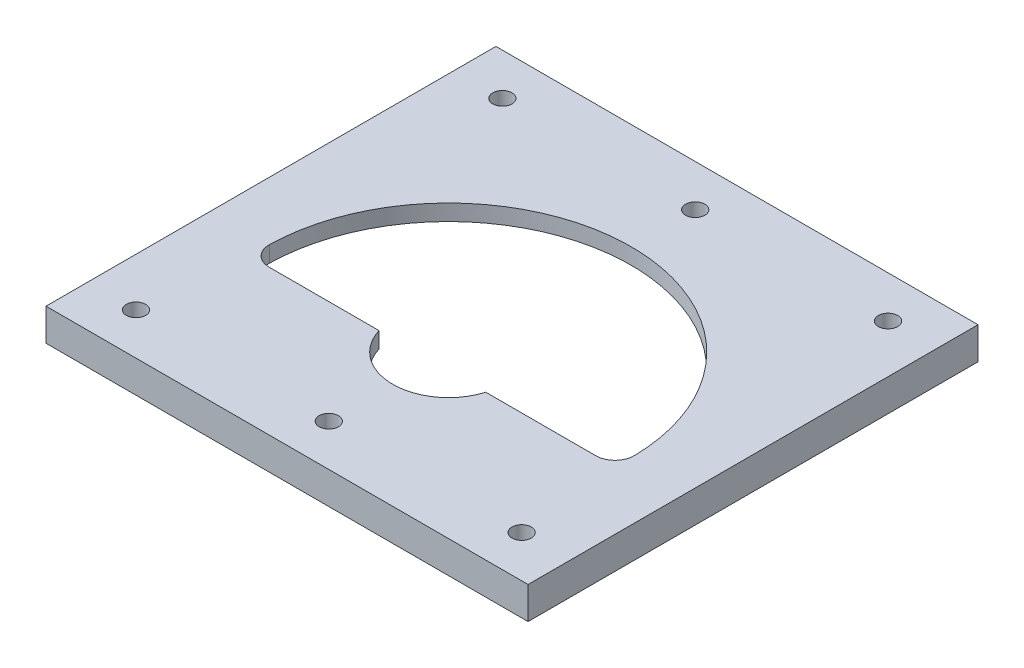
SolidWorks part; units mm, degrees
ref_plane "Front" through (0, 0, 0) normal (0, 0, 1) x (1, 0, 0)
ref_plane "Top" through (0, 0, 0) normal (0, 1, 0) x (1, 0, 0)
ref_plane "Right" through (0, 0, 0) normal (1, 0, 0) x (0, 0, -1)
sketch "Sketch1" plane through (0, 0, 0) normal (0, 1, 0) x (1, 0, 0)
  line L6 (-37.5, -25.1175) -> (37.5, -25.1175)
  line L8 (-37.5, -25.1175) -> (-37.5, 44.8825)
  line L9 (-37.5, 44.8825) -> (37.5, 44.8825)
  line L10 (37.5, -25.1175) -> (37.5, 44.8825)
  line L12 (0, 0) -> (0, 12.0208) construction
  line L13 (-25.41, -7) -> (-11.1616, -7) construction
  line L14 (11.1616, -7) -> (25.41, -7) construction
  line L15 (-12.0208, 12.0208) -> (12.0208, 12.0208) construction
  line L16 (-25.41, -7.5) -> (-11.4348, -7.5) construction
  line L17 (11.4348, -7.5) -> (25.41, -7.5) construction
  line L18 (-25.41, -2.5) -> (-8.307, -2.5)
  line L19 (8.307, -2.5) -> (25.41, -2.5)
  circle A4 centre (0, 0) radius 3.175 construction
  circle A5 centre (12.0208, 12.0208) radius 4.7625 construction
  circle A6 centre (-12.0208, 12.0208) radius 4.7625 construction
  arc A7 (32.9086, 0.6476) -> (-32.9086, 0.6476) centre (0, 0) ccw construction
  arc A8 (-32.9086, 0.6476) -> (-25.41, -7) centre (-25.41, 0.5) ccw construction
  arc A9 (-11.1616, -7) -> (11.1616, -7) centre (0, 0) ccw construction
  arc A10 (25.41, -7) -> (32.9086, 0.6476) centre (25.41, 0.5) ccw construction
  arc A11 (33.4085, 0.6574) -> (-33.4085, 0.6574) centre (0, 0) ccw construction
  arc A12 (-33.4085, 0.6574) -> (-25.41, -7.5) centre (-25.41, 0.5) ccw construction
  arc A13 (-11.4348, -7.5) -> (11.4348, -7.5) centre (0, 0) ccw construction
  arc A14 (25.41, -7.5) -> (33.4085, 0.6574) centre (25.41, 0.5) ccw construction
  arc A15 (28.4094, 0.559) -> (-28.4094, 0.559) centre (0, 0) ccw
  arc A16 (-28.4094, 0.559) -> (-25.41, -2.5) centre (-25.41, 0.5) ccw
  arc A17 (-8.307, -2.5) -> (8.307, -2.5) centre (0, 0) ccw
  arc A18 (25.41, -2.5) -> (28.4094, 0.559) centre (25.41, 0.5) ccw
  point P0 (0, 0)
  dimension "D1" = 12.0208
  dimension "D3" = 0.5
  dimension "D2" = 24.0416
  dimension "D4" = 5
  dimension "D6" = 70
  dimension "D7" = 75
extrude "Boss-Extrude1" add sketch "Sketch1" along normal blind 5
sketch "Sketch2" plane through (0, 5, 0) normal (0, 1, 0) x (1, 0, 0)
  line L0 (-30, -18.6175) -> (30, -18.6175) construction
  line L1 (-30, -18.6175) -> (-30, 38.3825) construction
  line L2 (-30, 38.3825) -> (30, 38.3825) construction
  line L3 (30, -18.6175) -> (30, 38.3825) construction
  line L4 (-30, -18.6175) -> (30, 38.3825) construction
  line L5 (-30, 38.3825) -> (30, -18.6175) construction
  line L6 (0, 38.3825) -> (0, 28.94) construction
  line L7 (0, -18.6175) -> (0, -9.175) construction
  circle A6 centre (-30, 38.3825) radius 1.5
  circle A7 centre (-30, -18.6175) radius 1.5
  circle A8 centre (0, -18.6175) radius 1.5
  circle A9 centre (30, -18.6175) radius 1.5
  circle A10 centre (30, 38.3825) radius 1.5
  circle A11 centre (0, 38.3825) radius 1.5
  arc A12 (28.8708, -2) -> (-28.8708, -2) centre (0, 0) ccw construction
  arc A13 (-8.9544, -2) -> (8.9544, -2) centre (0, 0) ccw construction
  point P10 (0, 9.8825)
  dimension "D3" = 3
  dimension "D1" = 57
  dimension "D2" = 60
extrude "Cut-Extrude1" cut sketch "Sketch2" against normal through all
sketch "Sketch3" plane through (0, 0, 0) normal (0, -1, 0) x (1, 0, 0)
  line L4 (25.41, 7.5) -> (11.4348, 7.5)
  line L5 (-11.4348, 7.5) -> (-25.41, 7.5)
  line L10 (25.41, 7.5) -> (11.4348, 7.5)
  line L11 (-11.4348, 7.5) -> (-25.41, 7.5)
  arc A10 (11.4348, 7.5) -> (-11.4348, 7.5) centre (0, 0) ccw
  arc A11 (33.4085, -0.6574) -> (25.41, 7.5) centre (25.41, -0.5) ccw
  arc A12 (-33.4085, -0.6574) -> (33.4085, -0.6574) centre (0, 0) ccw
  arc A13 (-25.41, 7.5) -> (-33.4085, -0.6574) centre (-25.41, -0.5) ccw
  arc A18 (11.4348, 7.5) -> (-11.4348, 7.5) centre (0, 0) ccw
  arc A19 (33.4085, -0.6574) -> (25.41, 7.5) centre (25.41, -0.5) ccw
  arc A20 (-33.4085, -0.6574) -> (33.4085, -0.6574) centre (0, 0) ccw
  arc A21 (-25.41, 7.5) -> (-33.4085, -0.6574) centre (-25.41, -0.5) ccw
  dimension "D1" = 5
extrude "Cut-Extrude3" cut sketch "Sketch3" against normal blind 2.5
